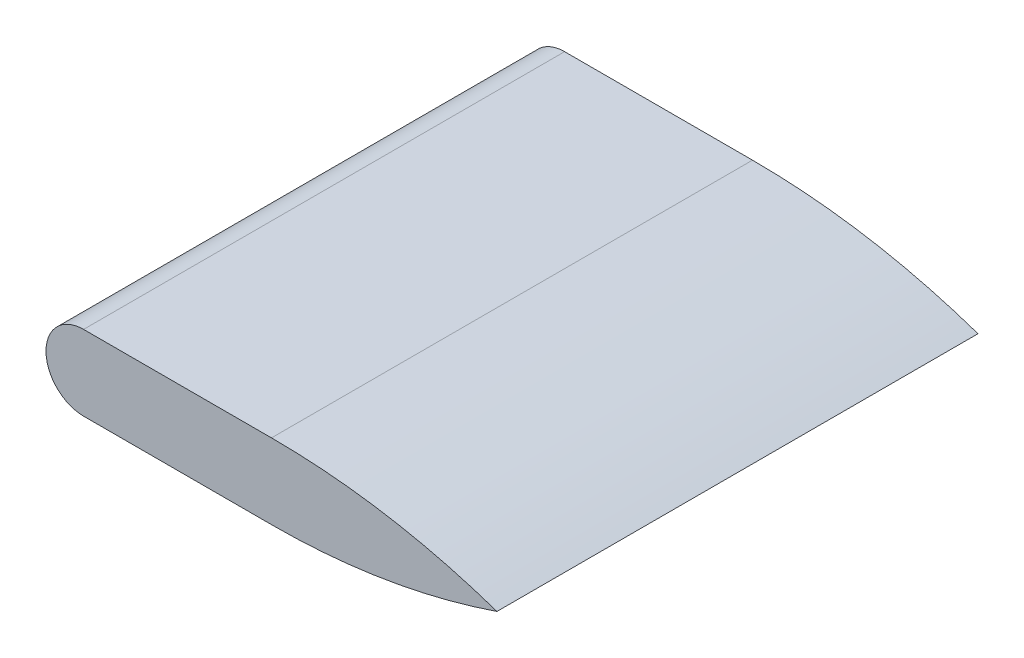
SolidWorks part; units mm, degrees
ref_plane "Plan de face" through (0, 0, 0) normal (0, 0, 1) x (1, 0, 0)
ref_plane "Plan de dessus" through (0, 0, 0) normal (0, 1, 0) x (1, 0, 0)
ref_plane "Plan de droite" through (0, 0, 0) normal (1, 0, 0) x (0, 0, -1)
sketch "Esquisse1" plane through (0, 0, 0) normal (0, 0, 1) x (1, 0, 0)
  line L0 (-39.7405, 26.2357) -> (-9.7405, 26.2357) construction
  line L1 (-37.2405, 28.7357) -> (-24.7405, 28.7357)
  line L3 (-37.2405, 23.7357) -> (-24.7405, 23.7357)
  line L5 (-24.7405, 28.7357) -> (-24.7405, 23.7357) construction
  arc A0 (-37.2405, 28.7357) -> (-37.2405, 23.7357) centre (-37.2405, 26.2357) ccw
  arc A1 (-9.7405, 26.2357) -> (-24.7405, 28.7357) centre (-24.7405, -17.5143) ccw
  arc A3 (-24.7405, 23.7357) -> (-9.7405, 26.2357) centre (-24.7405, 69.9857) ccw
  dimension "D1" = 5
  dimension "D2" = 30
  dimension "D3" = 15
extrude "Boss.-Extru.1" add sketch "Esquisse1" along normal blind 32
sketch "Esquisse3" plane through (0, 0, 0) normal (0, 0, -1) x (-1, 0, 0)
  line L0 (39.7405, 26.2357) -> (29.7405, 26.2357) construction
  line L2 (9.7405, 26.2357) -> (28.3032, 26.2357) construction
  line L3 (37.2405, 25.2357) -> (27.2405, 25.2357)
  line L5 (37.2405, 27.2357) -> (27.2405, 27.2357)
  line L6 (27.2405, 25.2357) -> (27.2405, 27.2357)
  arc A1 (37.2405, 25.2357) -> (37.2405, 27.2357) centre (37.2405, 26.2357) ccw
  arc A2 (37.2405, 23.7357) -> (37.2405, 28.7357) centre (37.2405, 26.2357) ccw construction
  dimension "D1" = 2
  dimension "D2" = 10
extrude "Enlèv. mat.-Extru.2" cut sketch "Esquisse3" against normal blind 25
